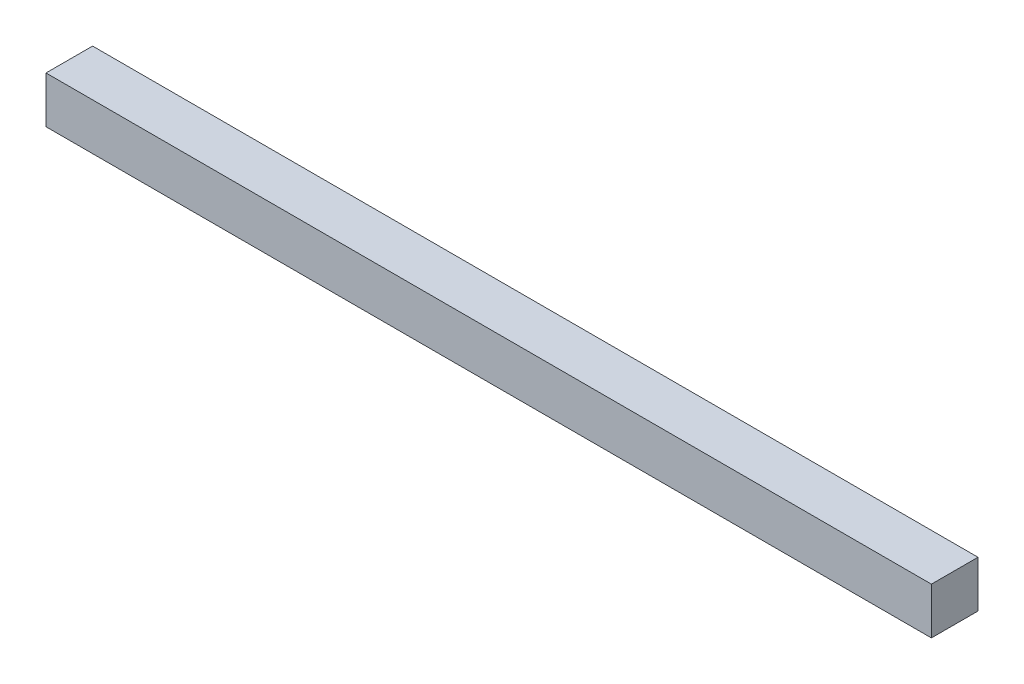
SolidWorks part; units mm, degrees
material "1023 Carbon Steel Sheet (SS)"
ref_plane "Front Plane" through (0, 0, 0) normal (0, 0, 1) x (1, 0, 0)
ref_plane "Top Plane" through (0, 0, 0) normal (0, 1, 0) x (1, 0, 0)
ref_plane "Right Plane" through (0, 0, 0) normal (1, 0, 0) x (0, 0, -1)
sketch "Sketch1" plane through (0, 0, 0) normal (0, 1, 0) x (1, 0, 0)
  line L1 (-53.9406, 28.944) -> (187.3594, 28.944)
  line L2 (-53.9406, 28.944) -> (-53.9406, 16.244)
  line L3 (-53.9406, 16.244) -> (187.3594, 16.244)
  line L4 (187.3594, 28.944) -> (187.3594, 16.244)
  dimension "D1" = 241.3
  dimension "D2" = 12.7
extrude "Boss-Extrude1" add sketch "Sketch1" along normal blind 12.7
sketch "Sketch2" plane through (0, 12.7, 0) normal (0, 1, 0) x (1, 0, 0)
  line L0 (187.3594, 28.944) -> (-53.9406, 28.944) construction
  line L1 (60.3594, 28.944) -> (73.0594, 28.944)
  line L2 (60.3594, 28.944) -> (60.3594, 16.244)
  line L3 (60.3594, 16.244) -> (73.0594, 16.244)
  line L4 (73.0594, 28.944) -> (73.0594, 16.244)
  line L5 (-53.9406, 16.244) -> (187.3594, 16.244) construction
  line L6 (-53.9406, 28.944) -> (-53.9406, 16.244) construction
  dimension "D1" = 12.7
  dimension "D2" = 114.3
equation "\"D2@Sketch2\"=(\"D1@Sketch1\"-\"D1@Sketch2\")/2"
